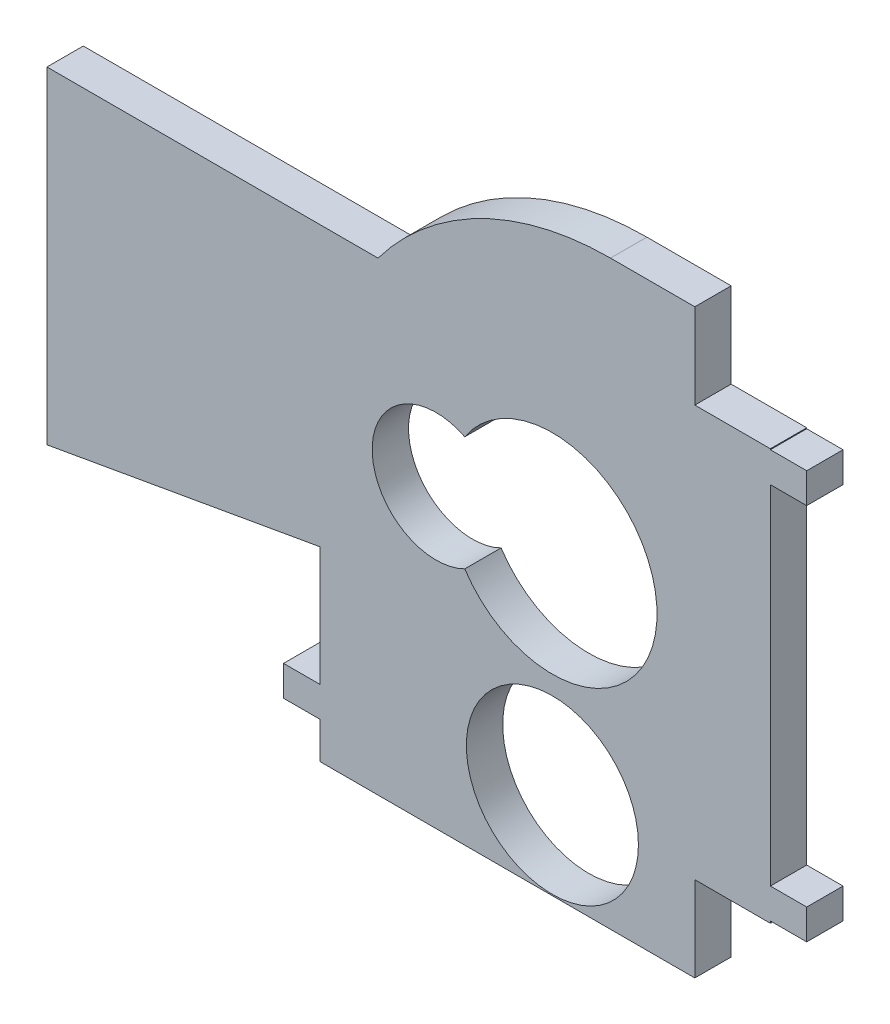
SolidWorks part; units mm, degrees
material "Balsa"
ref_plane "Front Plane" through (0, 0, 0) normal (0, 0, 1) x (1, 0, 0)
ref_plane "Top Plane" through (0, 0, 0) normal (0, 1, 0) x (1, 0, 0)
ref_plane "Right Plane" through (0, 0, 0) normal (1, 0, 0) x (0, 0, -1)
sketch "Sketch1" plane through (0, 0, 0) normal (0, 0, 1) x (1, 0, 0)
  line L0 (0, -1000.1535) -> (0, 48999.8465) construction
  line L1 (0, 9.144) -> (-5.08, 9.144) construction
  line L2 (-1000, 0) -> (49000, 0) construction
  line L3 (9.525, 16.51) -> (11.1125, 16.51)
  line L4 (2.54, 21.59) -> (9.525, 21.59)
  line L5 (-10.16, 8.89) -> (-10.16, -3.81)
  line L6 (-10.16, -3.81) -> (9.525, -3.81)
  line L7 (9.525, 21.59) -> (9.525, -3.81)
  line L8 (-11.7475, -2.2098) -> (-10.16, -2.2098)
  line L9 (-11.7475, -2.2098) -> (-11.7475, -0.889)
  line L10 (-11.7475, -0.889) -> (-10.16, -0.889)
  line L11 (-10.16, -2.2098) -> (-10.16, -0.889)
  line L12 (9.525, 0) -> (11.1125, 0)
  line L13 (9.525, 0) -> (9.525, 1.3208)
  line L14 (9.525, 1.3208) -> (11.1125, 1.3208)
  line L15 (11.1125, 0) -> (11.1125, 1.3208)
  line L16 (9.525, 16.51) -> (9.525, 17.8308)
  line L17 (9.525, 17.8308) -> (11.1125, 17.8308)
  line L18 (11.1125, 16.51) -> (11.1125, 17.8308)
  line L19 (-7.62, 16.51) -> (-22.0849, 16.51)
  line L21 (-22.0849, 2.212) -> (-10.16, 4.318)
  line L22 (9.525, 8.89) -> (-35.5862, 8.89) construction
  line L31 (-22.0849, 16.51) -> (-22.0849, 2.212)
  circle A0 centre (0, 0) radius 3.7592
  arc A1 (-3.829, 6.6457) -> (-3.829, 11.6423) centre (0, 9.144) ccw
  arc A2 (-3.829, 11.6423) -> (-3.829, 6.6457) centre (-5.08, 9.144) ccw
  arc A3 (2.54, 21.59) -> (-10.16, 8.89) centre (2.54, 8.89) ccw
  point P33 (9.525, 8.89)
  point P35 (-27.4189, 8.89)
  dimension "D1" = 7.5184
  dimension "D4" = 3.81
  dimension "D3" = 9.144
  dimension "D5" = 2.794
  dimension "D9" = 12.7
  dimension "D10" = 1.5875
  dimension "D2" = 25.4
  dimension "D6" = 9.525
  dimension "D7" = 5.08
  dimension "D8" = 19.685
  dimension "D11" = 9.144
  dimension "D12" = 1.3208
  dimension "D13" = 1.3208
  dimension "D14" = 1.5875
  dimension "D15" = 2
  dimension "D16" = 8.128
  dimension "D17" = 2.106
  dimension "D18" = 11.9249
  dimension "D19" = 5.08
  dimension "D20" = 5.207
extrude "Boss-Extrude1" add sketch "Sketch1" along normal blind 1.5875
sketch "Sketch2" plane through (0, 0, 1.5875) normal (0, 0, 1) x (1, 0, 0)
  line L0 (9.525, -0.9144) -> (9.525, -3.0226) construction
  line L1 (6.223, -3.8481) -> (9.525, -3.8481)
  line L2 (6.223, -3.8481) -> (6.223, -0.0889)
  line L3 (6.223, -0.0889) -> (9.525, -0.0889)
  line L4 (9.525, -3.8481) -> (9.525, -0.0889)
  line L5 (9.525, -0.9144) -> (9.525, -3.0226)
  line L6 (9.525, 20.8026) -> (9.525, 18.6944) construction
  line L7 (9.525, 20.8026) -> (9.525, 18.6944)
  line L9 (6.223, 17.8689) -> (9.525, 17.8689)
  line L10 (6.223, 17.8689) -> (6.223, 21.6281)
  line L11 (6.223, 21.6281) -> (9.525, 21.6281)
  line L12 (9.525, 17.8689) -> (9.525, 21.6281)
  point P8 (9.525, -1.9685)
  point P9 (9.525, -1.9685)
  point P10 (9.525, 19.7485)
  point P15 (9.525, 19.7485)
  line M4 (9.525, 21.59) -> (2.54, 21.59)
  line M11 (-10.16, -3.81) -> (9.525, -3.81)
  line M12 (9.525, -3.81) -> (9.525, 0)
  line M20 (9.525, 17.8308) -> (9.525, 21.59)
  dimension "D1" = 3.7592
  dimension "D2" = 3.302
  dimension "D3" = 3.7592
  dimension "D4" = 3.302
extrude "Cut-Extrude1" cut sketch "Sketch2" against normal up to next contours L3 L2 L4 M11 M12 | L10 L9 M20 M4
move or copy body "Body-Move/Copy1" [suppressed]
